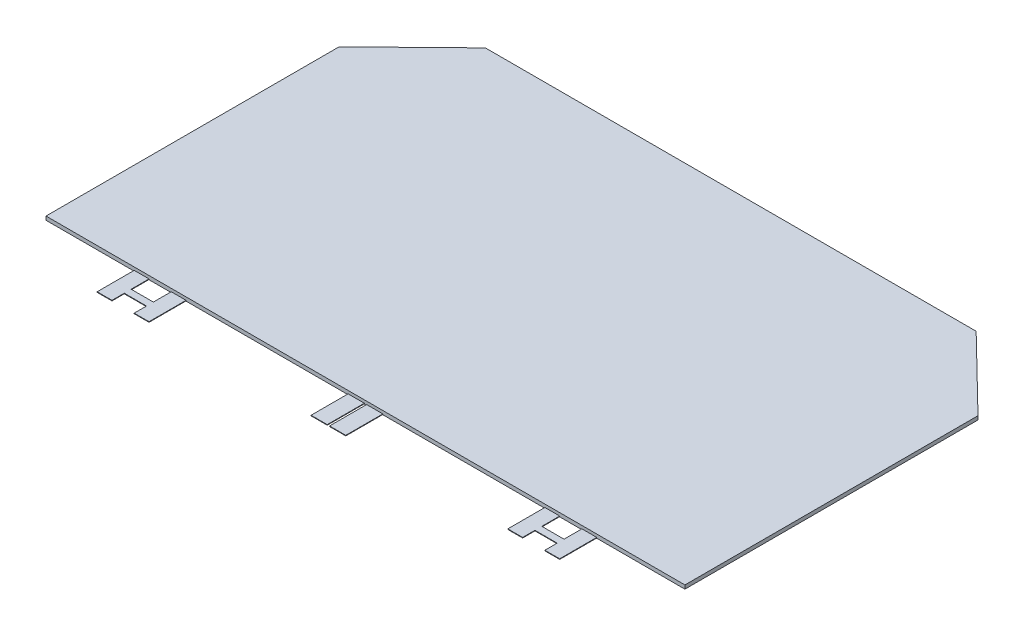
SolidWorks part; units mm, degrees
ref_plane "Front Plane" through (0, 0, 0) normal (0, 0, 1) x (1, 0, 0)
ref_plane "Top Plane" through (0, 0, 0) normal (0, 1, 0) x (1, 0, 0)
ref_plane "Right Plane" through (0, 0, 0) normal (1, 0, 0) x (0, 0, -1)
sketch "Sketch1" plane through (0, 0, 0) normal (0, 1, 0) x (1, 0, 0)
  line L0 (0, 31.65) -> (8, 39.45)
  line L1 (0, 0) -> (69, 0)
  line L2 (0, 0) -> (0, 39.45)
  line L3 (0, 39.45) -> (69, 39.45)
  line L4 (69, 0) -> (69, 39.45)
  line L5 (8, 39.45) -> (61, 39.45)
  line L6 (61, 39.45) -> (69, 31.65)
  line L7 (0, 31.65) -> (69, 31.65) construction
  line L8 (8, 39.45) -> (0, 39.45) construction
  line L9 (61, 39.45) -> (69, 39.45) construction
  point P7 (11.6356, 39.45)
  dimension "D1" = 69
  dimension "D2" = 39.45
  dimension "D3" = 31.65
  dimension "D4" = 53
extrude "Boss-Extrude1" add sketch "Sketch1" along normal blind 0.4 contours L6 L3 L0 L2 L1 L4
ref_plane "Plane1" through (0, 0.02, 0) normal (0, -1, 0) x (-1, 0, 0)
sketch "Sketch2" plane through (0, 0.02, 0) normal (0, -1, 0) x (1, 0, 0)
  line L0 (0, 0) -> (69, 0) construction
  line L1 (9.525, 0) -> (11.125, 0)
  line L2 (9.525, 0) -> (9.525, 4)
  line L3 (9.525, 4) -> (11.125, 4)
  line L4 (11.125, 0) -> (11.125, 4)
  line L5 (57.875, 0) -> (59.475, 0)
  line L6 (57.875, 0) -> (57.875, 4)
  line L7 (57.875, 4) -> (59.475, 4)
  line L8 (59.475, 0) -> (59.475, 4)
  line L9 (32.625, 0) -> (34.375, 0)
  line L10 (32.625, 0) -> (32.625, 4)
  line L11 (32.625, 4) -> (34.375, 4)
  line L12 (34.375, 0) -> (34.375, 4)
  line L13 (13.525, 0) -> (15.125, 0)
  line L14 (13.525, 0) -> (13.525, 4)
  line L15 (13.525, 4) -> (15.125, 4)
  line L16 (15.125, 0) -> (15.125, 4)
  line L17 (53.875, 0) -> (55.475, 0)
  line L18 (53.875, 0) -> (53.875, 4)
  line L19 (53.875, 4) -> (55.475, 4)
  line L20 (55.475, 0) -> (55.475, 4)
  line L21 (34.625, 0) -> (36.375, 0)
  line L22 (34.625, 0) -> (34.625, 4)
  line L23 (34.625, 4) -> (36.375, 4)
  line L24 (36.375, 0) -> (36.375, 4)
  line L25 (34.375, 0) -> (34.625, 0)
  line L26 (55.475, 1.93) -> (57.875, 1.93)
  line L27 (55.475, 1.93) -> (55.475, 2.67)
  line L28 (55.475, 2.67) -> (57.875, 2.67)
  line L29 (57.875, 1.93) -> (57.875, 2.67)
  line L30 (11.125, 1.93) -> (13.525, 1.93)
  line L31 (11.125, 1.93) -> (11.125, 2.67)
  line L32 (11.125, 2.67) -> (13.525, 2.67)
  line L33 (13.525, 1.93) -> (13.525, 2.67)
  line L34 (11.125, 0) -> (13.525, 0)
  line L35 (55.475, 0) -> (57.875, 0)
  line L36 (15.125, 4) -> (32.625, 4) construction
  line L37 (36.375, 4) -> (53.875, 4) construction
  point P26 (58.675, 0)
  point P37 (34.5, 0)
  dimension "D1" = 1.6
  dimension "D2" = 1.75
  dimension "D3" = 0.25
  dimension "D4" = 4
  dimension "D5" = 2.4
  dimension "D6" = 2.4
  dimension "D7" = 1.93
  dimension "D8" = 2.67
  dimension "D9" = 38.75
extrude "Boss-Extrude2" add sketch "Sketch2" against normal blind 0.06 separate body
